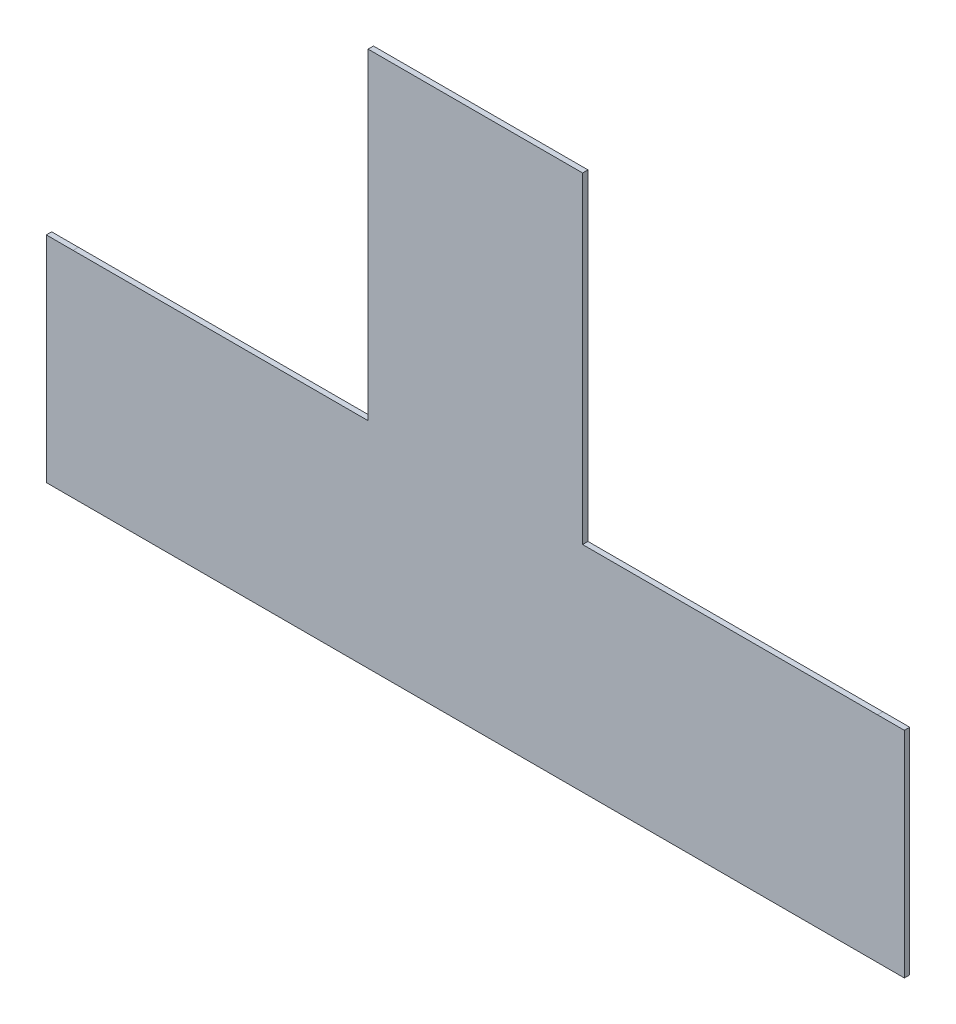
SolidWorks part; units mm, degrees
ref_plane "Front Plane" through (0, 0, 0) normal (0, 0, 1) x (1, 0, 0)
ref_plane "Top Plane" through (0, 0, 0) normal (0, 1, 0) x (1, 0, 0)
ref_plane "Right Plane" through (0, 0, 0) normal (1, 0, 0) x (0, 0, -1)
sketch "Sketch1" plane through (0, 0, 0) normal (0, 0, 1) x (1, 0, 0)
  line L0 (800, 1000) -> (800, 0)
  line L1 (0, 0) -> (1600, 0)
  line L2 (0, 0) -> (0, 400)
  line L3 (0, 400) -> (600, 400)
  line L6 (600, 400) -> (600, 1000)
  line L7 (600, 1000) -> (1000, 1000)
  line L9 (1000, 400) -> (1000, 1000)
  line L10 (1600, 400) -> (1000, 400)
  line L11 (1600, 0) -> (1600, 400)
  dimension "D1" = 400
  dimension "D2" = 600
  dimension "D3" = 1000
  dimension "D4" = 1600
extrude "Boss-Extrude1" add sketch "Sketch1" along normal blind 10 contours L7 L6 L3 L2 L1 L0 | L1 L11 L10 L9 L7 L0
ref_plane "Plane1" through (0, 400, 0) normal (0, 1, 0) x (1, 0, 0)
sketch "Sketch2" plane through (0, 400, 0) normal (0, 1, 0) x (1, 0, 0)
  line L0 (1600, 0) -> (1000, 0) construction
  line L1 (1550, 0) -> (1600, 0)
  line L2 (1550, 0) -> (1550, -10)
  line L3 (1550, -10) -> (1600, -10)
  line L4 (1600, 0) -> (1600, -10)
  line L5 (1600, -10) -> (1600, 0) construction
  line L6 (1600, -10) -> (1000, -10) construction
  line L7 (0, -10) -> (600, -10) construction
  line L8 (0, 0) -> (50, 0)
  line L9 (0, 0) -> (0, -10)
  line L10 (0, -10) -> (50, -10)
  line L11 (50, 0) -> (50, -10)
  dimension "D1" = 50
  dimension "D2" = 50
split line "Split Line1"
